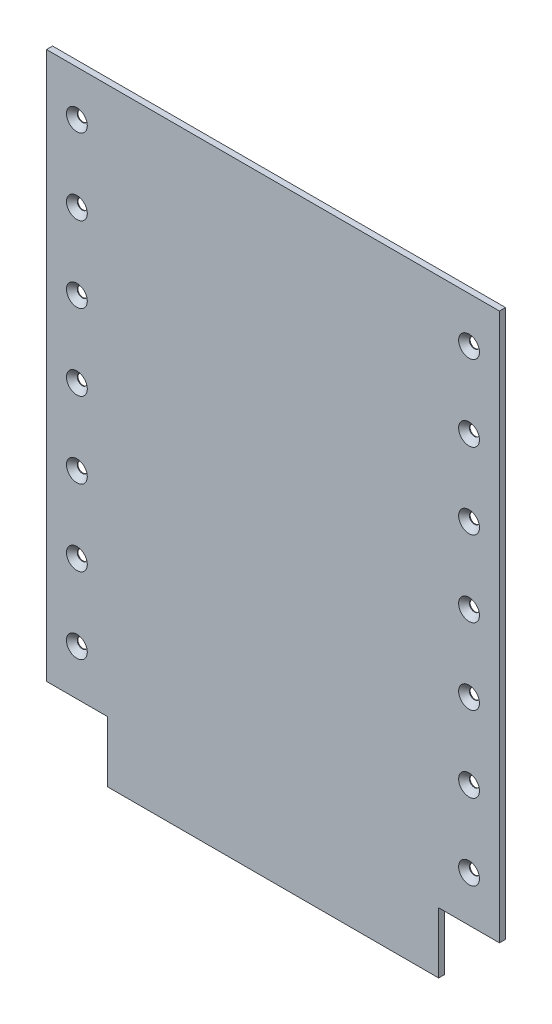
SolidWorks part; units mm, degrees
material "Фанера, берёза, ФСФ ВВ/С ГОСТ 3916.1-96"
ref_plane "Спереди" through (0, 0, 0) normal (0, 0, 1) x (1, 0, 0)
ref_plane "Сверху" through (0, 0, 0) normal (0, 1, 0) x (1, 0, 0)
ref_plane "Справа" through (0, 0, 0) normal (1, 0, 0) x (0, 0, -1)
sketch "Эскиз1" plane through (0, 0, 0) normal (0, 0, 1) x (1, 0, 0)
  line L0 (0, 400) -> (-40, 400)
  line L1 (0, 0) -> (218, 0)
  line L2 (-40, 400) -> (-40, 40)
  line L3 (0, 400) -> (218, 400)
  line L4 (-40, 40) -> (0, 40)
  line L5 (0, 40) -> (0, 0)
  line L6 (218, 40) -> (218, 0)
  line L7 (109, 400) -> (109, 0) construction
  line L8 (258, 40) -> (218, 40)
  line L9 (258, 400) -> (258, 40)
  line L10 (218, 400) -> (258, 400)
  dimension "D1" = 400
  dimension "D2" = 218
  dimension "D3" = 40
  dimension "D4" = 40
extrude "Бобышка-Вытянуть1" add sketch "Эскиз1" along normal blind 4
hole_wizard "Зенковка для винта с потайной головкой и внутренним шестигранником M61" positions "Эскиз3" profile "Эскиз2" countersink size "M6" standard "DIN" end condition through all
sketch "Эскиз3" plane through (0, 0, 4) normal (0, 0, 1) x (1, 0, 0)
  line L0 (258, 40) -> (258, 400) construction
  line L1 (-40, 400) -> (-40, 40) construction
  line L2 (-20, 70) -> (-20, 120) construction
  line L3 (238, 70) -> (238, 40)
  line L7 (238, 370) -> (238, 400)
  line L8 (258, 400) -> (-40, 400) construction
  line L10 (218, 40) -> (258, 40) construction
  point P0 (238, 70)
  point P5 (-20, 70)
  point P18 (238, 120)
  point P19 (-20, 120)
  point P20 (238, 170)
  point P21 (-20, 170)
  point P22 (238, 220)
  point P23 (-20, 220)
  point P24 (238, 270)
  point P25 (-20, 270)
  point P26 (238, 320)
  point P27 (-20, 320)
  point P28 (238, 370)
  point P29 (-20, 370)
  dimension "D1" = 20
  dimension "D2" = 20
  dimension "D4" = 50
  dimension "D3" = 7
sketch "Эскиз2" plane through (238, 70, 4) normal (1, 0, 0) x (0, -1, 0)
  line L0 (0, 0) -> (0, 4)
  line L1 (0, 4) -> (3.3, 4)
  line L2 (3.3, 4) -> (3.3, 3.555)
  line L3 (3.3, 3.555) -> (6.855, 0)
  line L5 (6.855, 0) -> (0, 0)
  line L6 (-3.3, 3.555) -> (-6.855, 0) construction
  line L11 (0, -6.35) -> (0, 107.95) construction
  dimension "Диаметр сквозного отверстия" = 6.6
  dimension "Глубина сквозного отверстия" = 4
  dimension "Диаметр передней зенковки" = 13.71
  dimension "Угол передней зенковки" = 90
